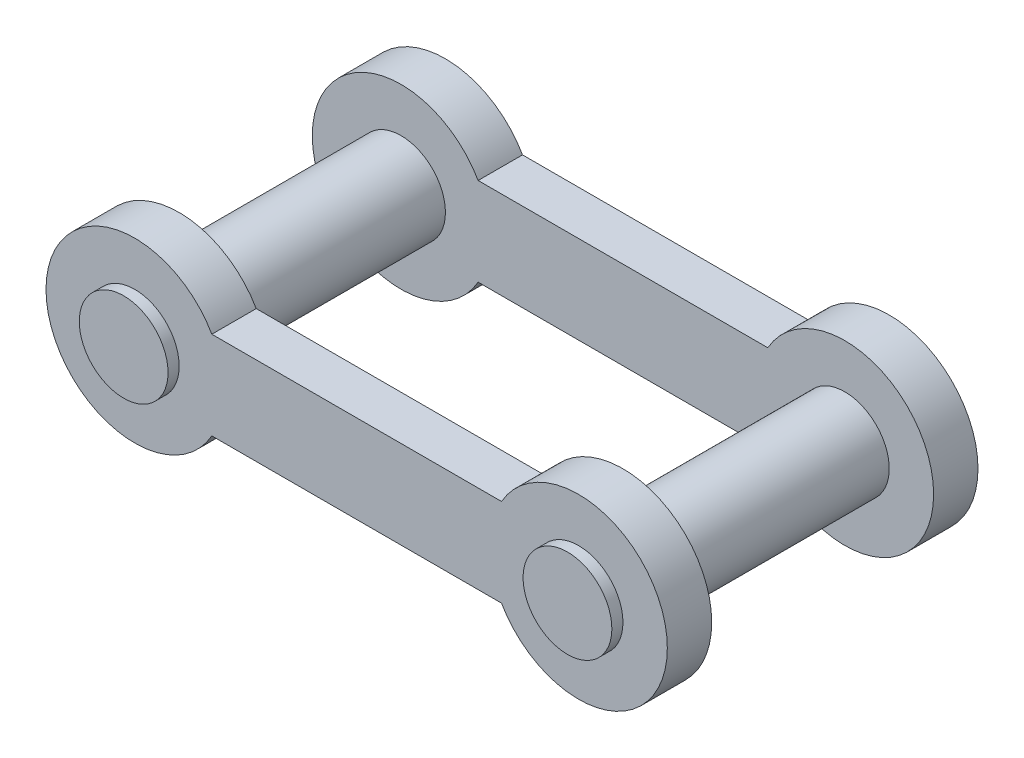
SolidWorks part; units mm, degrees
ref_plane "前视基准面" through (0, 0, 0) normal (0, 0, 1) x (1, 0, 0)
ref_plane "上视基准面" through (0, 0, 0) normal (0, 1, 0) x (1, 0, 0)
ref_plane "右视基准面" through (0, 0, 0) normal (1, 0, 0) x (0, 0, -1)
sketch "草图1" plane through (0, 0, 0) normal (0, 0, 1) x (1, 0, 0)
  line L0 (0, 0) -> (0, 0.8208) construction
  line L1 (0, 0.8208) -> (0, -0.6616) construction
  line L2 (0, 0) -> (-1.1256, 0) construction
  line L3 (-1.1256, 0) -> (1.4655, 0) construction
  line L4 (-6.5266, 1.9838) -> (6.5266, 1.9838)
  line L5 (-6.5266, -1.9838) -> (6.5266, -1.9838)
  arc A0 (-6.5266, 1.9838) -> (-6.5266, -1.9838) centre (-10, 0) ccw
  circle A1 centre (-10, 0) radius 2
  circle A2 centre (10, 0) radius 2
  arc A3 (6.5266, 1.9838) -> (6.5266, -1.9838) centre (10, 0) cw
  dimension "D2" = 8
  dimension "D3" = 4
  dimension "D1" = 10
extrude "凸台-拉伸1" add sketch "草图1" along normal blind 2
sketch "草图2" plane through (0, 0, 2) normal (0, 0, 1) x (1, 0, 0)
  circle A0 centre (10, 0) radius 2 construction
  circle A1 centre (-10, 0) radius 2 construction
  circle A2 centre (10, 0) radius 2
  circle A3 centre (-10, 0) radius 2
extrude "凸台-拉伸2" add sketch "草图2" along normal blind 12.5 and the other way blind 2.5
ref_plane "基准面1" through (0, 0, 7) normal (0, 0, 1) x (1, 0, 0)
mirror "镜向1" about plane through (0, 0, 7) normal (0, 0, 1) of "凸台-拉伸1"
